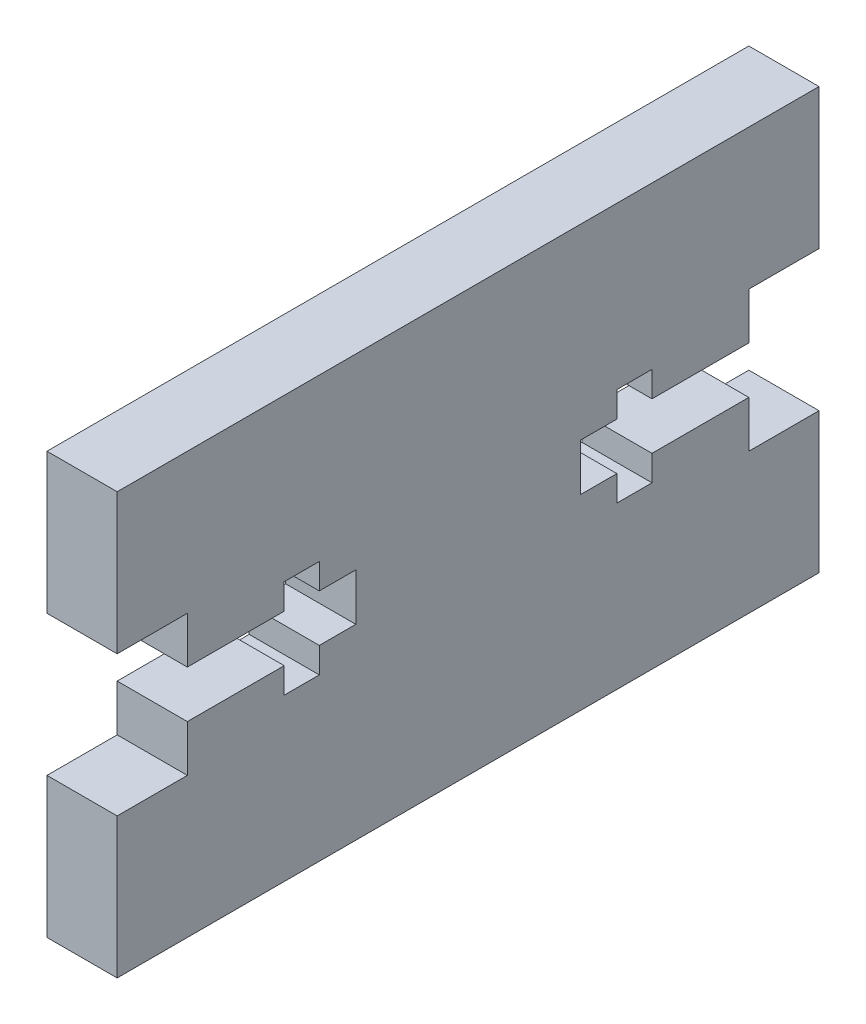
SolidWorks part; units mm, degrees
ref_plane "Front Plane" through (0, 0, 0) normal (0, 0, 1) x (1, 0, 0)
ref_plane "Top Plane" through (0, 0, 0) normal (0, 1, 0) x (1, 0, 0)
ref_plane "Right Plane" through (0, 0, 0) normal (1, 0, 0) x (0, 0, -1)
sketch "Sketch1" plane through (0, 0, 0) normal (0, 0, 1) x (1, 0, 0)
  line L0 (-17.78, 19.05) -> (17.78, 19.05) construction
  line L1 (-17.78, -19.05) -> (-11.43, -19.05)
  line L2 (-17.78, -19.05) -> (-17.78, 19.05)
  line L3 (-17.78, 19.05) -> (-11.43, 19.05)
  line L4 (-11.43, -19.05) -> (-11.43, 19.05)
  dimension "D1" = 6.35
extrude "Boss-Extrude1" add sketch "Sketch1" along normal blind 50.8
sketch "Sketch2" plane through (0, 0, 0) normal (0, 0, -1) x (-1, 0, 0)
  line L0 (11.43, -19.05) -> (11.43, 19.05) construction
  line L1 (17.78, -19.05) -> (11.43, -19.05)
  line L2 (17.78, -19.05) -> (17.78, -6.35)
  line L3 (17.78, -6.35) -> (11.43, -6.35)
  line L4 (11.43, -19.05) -> (11.43, -6.35)
  line L6 (17.78, 19.05) -> (11.43, 19.05)
  line L7 (17.78, 19.05) -> (17.78, 6.35)
  line L8 (17.78, 6.35) -> (11.43, 6.35)
  line L9 (11.43, 19.05) -> (11.43, 6.35)
  dimension "D1" = 12.7
extrude "Boss-Extrude2" add sketch "Sketch2" along normal blind 6.35
sketch "Sketch3" plane through (-17.78, 0, 0) normal (-1, 0, 0) x (0, 0, 1)
  line L0 (4.7891, 0) -> (14.9708, 0) construction
  line L2 (-6.35, -6.35) -> (0, -6.35) construction
  line L3 (-6.35, 6.35) -> (0, 6.35) construction
  line L4 (0, 6.35) -> (0, -6.35) construction
  line B0 (0, 2.1336) -> (0, -2.1336)
  line B1 (11.938, -2.1336) -> (11.938, -4.445)
  line B2 (11.938, -4.445) -> (8.763, -4.445)
  line B3 (8.763, -4.445) -> (8.763, -2.1336)
  line B4 (8.763, -2.1336) -> (0, -2.1336)
  line B5 (11.938, -2.1336) -> (15.24, -2.1336)
  line B6 (15.24, -2.1336) -> (15.24, 2.1336)
  line B7 (11.938, 2.1336) -> (15.24, 2.1336)
  line B8 (8.763, 2.1336) -> (0, 2.1336)
  line B9 (8.763, 4.445) -> (8.763, 2.1336)
  line B10 (11.938, 4.445) -> (8.763, 4.445)
  line B11 (11.938, 2.1336) -> (11.938, 4.445)
sketch_block_instance "TSlot-1"
sketch_block "TSlot" parameters "D1"=3.302, "D2"=3.175
extrude "Cut-Extrude1" cut sketch "Sketch3" against normal through all
ref_plane "midplane" through (0, 0, 25.4) normal (0, 0, 1) x (1, 0, 0)
mirror "Mirror1" about plane through (0, 0, 25.4) normal (0, 0, 1) of "Cut-Extrude1", "Boss-Extrude2"
